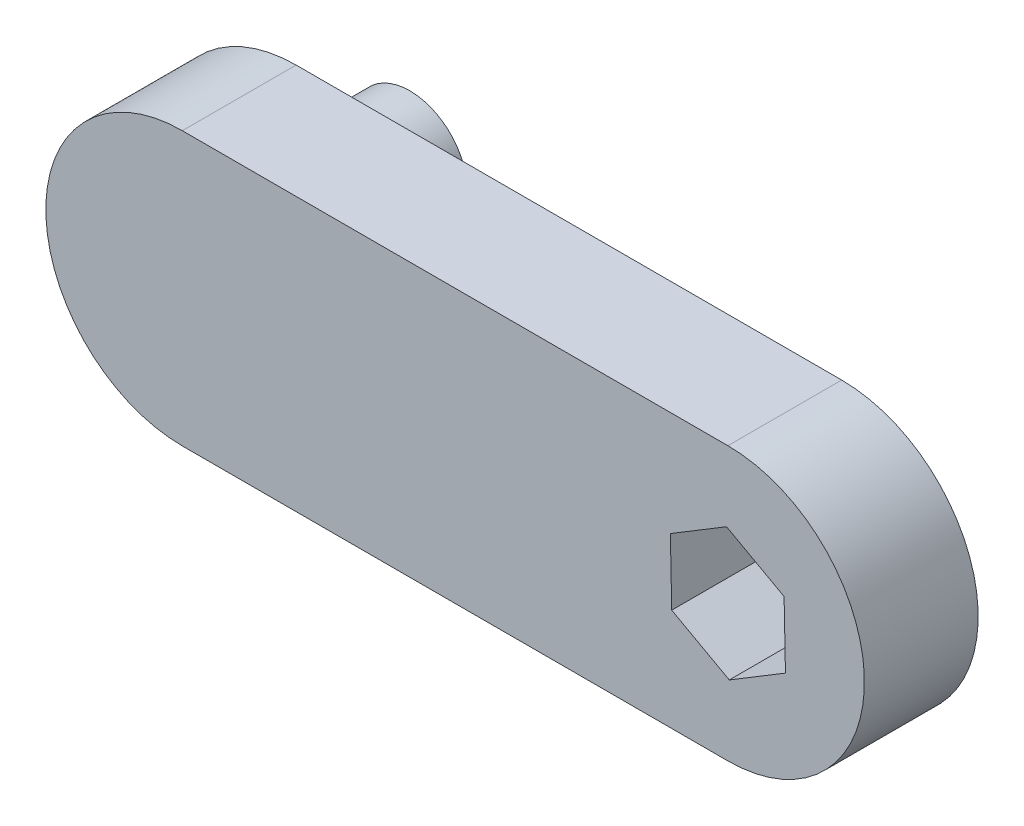
SolidWorks part; units mm, degrees
ref_plane "前视基准面" through (0, 0, 0) normal (0, 0, 1) x (1, 0, 0)
ref_plane "上视基准面" through (0, 0, 0) normal (0, 1, 0) x (1, 0, 0)
ref_plane "右视基准面" through (0, 0, 0) normal (1, 0, 0) x (0, 0, -1)
other "Configuration Table"
sketch "草图1" plane through (0, 0, 0) normal (0, 0, 1) x (1, 0, 0)
  line L0 (0, 0) -> (23.9796, 0) construction
  line L1 (0, 6) -> (23.9796, 6)
  line L2 (0, -6) -> (23.9796, -6)
  line L4 (26.509, -1.3912) -> (26.4491, 1.495)
  line L5 (26.4491, 1.495) -> (23.9197, 2.8861)
  line L6 (23.9197, 2.8861) -> (21.4501, 1.3912)
  line L7 (21.4501, 1.3912) -> (21.5101, -1.495)
  line L8 (21.5101, -1.495) -> (24.0395, -2.8861)
  line L9 (24.0395, -2.8861) -> (26.509, -1.3912)
  arc A0 (0, 6) -> (0, -6) centre (0, 0) ccw
  arc A1 (23.9796, -6) -> (23.9796, 6) centre (23.9796, 0) ccw
  circle A4 centre (23.9796, 0) radius 2.5 construction
  point P3 (11.9898, 0)
  dimension "D1" = 6
  dimension "D2" = 5
extrude "凸台-拉伸1" add sketch "草图1" along normal blind 5
sketch "草图3" plane through (0, 0, 0) normal (0, 0, -1) x (-1, 0, 0)
  circle A0 centre (0, 0) radius 2.52
  dimension "D1" = 5.04
extrude "凸台-拉伸3" add sketch "草图3" along normal blind 5
